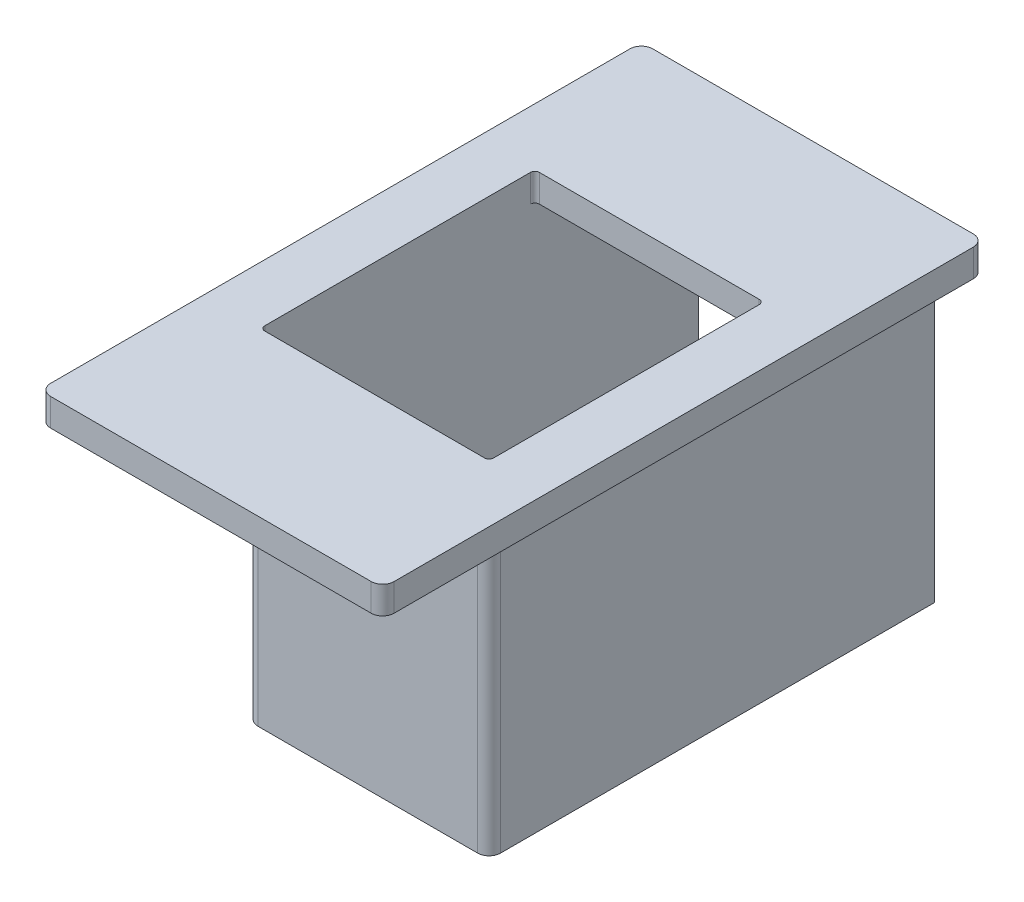
SolidWorks part; units mm, degrees
ref_plane "Alzado" through (0, 0, 0) normal (0, 0, 1) x (1, 0, 0)
ref_plane "Planta" through (0, 0, 0) normal (0, 1, 0) x (1, 0, 0)
ref_plane "Vista lateral" through (0, 0, 0) normal (1, 0, 0) x (0, 0, -1)
sketch "Croquis1" plane through (0, 0, 0) normal (0, 1, 0) x (1, 0, 0)
  line L0 (739.1914, -1296.0489) -> (750, -1315) construction
  line L1 (-700, 1315) -> (700, 1315)
  line L2 (-750, 1265) -> (-750, -1265)
  line L3 (-700, -1315) -> (700, -1315)
  line L4 (750, 1265) -> (750, -1265)
  line L5 (-750, 1315) -> (-739.1914, 1296.0489) construction
  line L6 (-750, -1315) -> (-739.1914, -1296.0489) construction
  line L7 (-500, 600) -> (500, 600)
  line L8 (-500, 600) -> (-500, -600)
  line L9 (-500, -600) -> (500, -600)
  line L10 (500, 600) -> (500, -600)
  line L11 (-500, 600) -> (500, -600) construction
  line L12 (-500, -600) -> (500, 600) construction
  line L13 (739.1914, 1296.0489) -> (750, 1315) construction
  arc A0 (700, 1315) -> (750, 1265) centre (700, 1265) cw
  arc A1 (700, -1315) -> (750, -1265) centre (700, -1265) ccw
  arc A2 (-750, -1265) -> (-700, -1315) centre (-700, -1265) ccw
  arc A3 (-700, 1315) -> (-750, 1265) centre (-700, 1265) ccw
  point P0 (0, 0)
  point P18 (0, 0)
  dimension "D3" = 50
  dimension "D1" = 2630
  dimension "D2" = 1500
  dimension "D4" = 1200
  dimension "D5" = 1000
extrude "Saliente-Extruir1" add sketch "Croquis1" along normal blind 120
fillet "Redondeo1" radius 20 4 edges at (-500, 60, 600) (-500, 60, -600) (500, 60, -600) (500, 60, 600)
sketch "Croquis2" plane through (0, 120, 0) normal (0, 1, 0) x (1, 0, 0)
  line L0 (-500, -580) -> (-500, 580)
  line L1 (-480, 600) -> (480, 600)
  line L2 (500, 580) -> (500, -580)
  line L3 (480, -600) -> (-480, -600)
  line L4 (-530, -580) -> (-530, 580)
  line L5 (-480, 630) -> (480, 630)
  line L6 (530, 580) -> (530, -580)
  line L7 (480, -630) -> (-480, -630)
  arc A0 (-500, 580) -> (-480, 600) centre (-480, 580) cw
  arc A1 (480, 600) -> (500, 580) centre (480, 580) cw
  arc A2 (500, -580) -> (480, -600) centre (480, -580) cw
  arc A3 (-480, -600) -> (-500, -580) centre (-480, -580) cw
  arc A4 (-530, 580) -> (-480, 630) centre (-480, 580) cw
  arc A5 (480, 630) -> (530, 580) centre (480, 580) cw
  arc A6 (530, -580) -> (480, -630) centre (480, -580) cw
  arc A7 (-480, -630) -> (-530, -580) centre (-480, -580) cw
  dimension "D1" = 30
extrude "Saliente-Extruir2" add sketch "Croquis2" against normal blind 1480
sketch "Croquis3" plane through (0, 0, 0) normal (0, -1, 0) x (1, 0, 0)
  line L0 (500, -580) -> (500, -1315)
  line L1 (530, -580) -> (530, -1315)
  line L3 (530, -580) -> (500, -580)
  line L4 (500, -1315) -> (530, -1315)
  line L5 (700, -1315) -> (-700, -1315) construction
  line L7 (-500, -1315) -> (-530, -1315)
  line L8 (-530, -580) -> (-530, -1315)
  line L9 (-500, -580) -> (-500, -1315)
  line L10 (-530, -580) -> (-500, -580)
extrude "Saliente-Extruir3" add sketch "Croquis3" along normal up to surface (1360 mm away) up to face at (0, -1360, 0)
sketch "Croquis4" plane through (0, -1360, 0) normal (0, -1, 0) x (1, 0, 0)
  line L0 (500, -580) -> (500, -639.7858)
  line L1 (500, -625.8258) -> (500, -1315) construction
  line L2 (500, -639.7858) -> (-500, -639.7858)
  line L3 (-500, -1315) -> (-500, -625.8258) construction
  line L4 (-500, -639.7858) -> (-500, -563.7318)
  line L5 (-500, -580) -> (-500, 580) construction
  line L6 (-500, -563.7318) -> (500, -563.7318)
  line L7 (500, 580) -> (500, -580) construction
  line L8 (500, -563.7318) -> (500, -580)
extrude "Cortar-Extruir1" cut sketch "Croquis4" against normal up to surface (1360 mm away) up to face at (0, 0, -857.2861)
